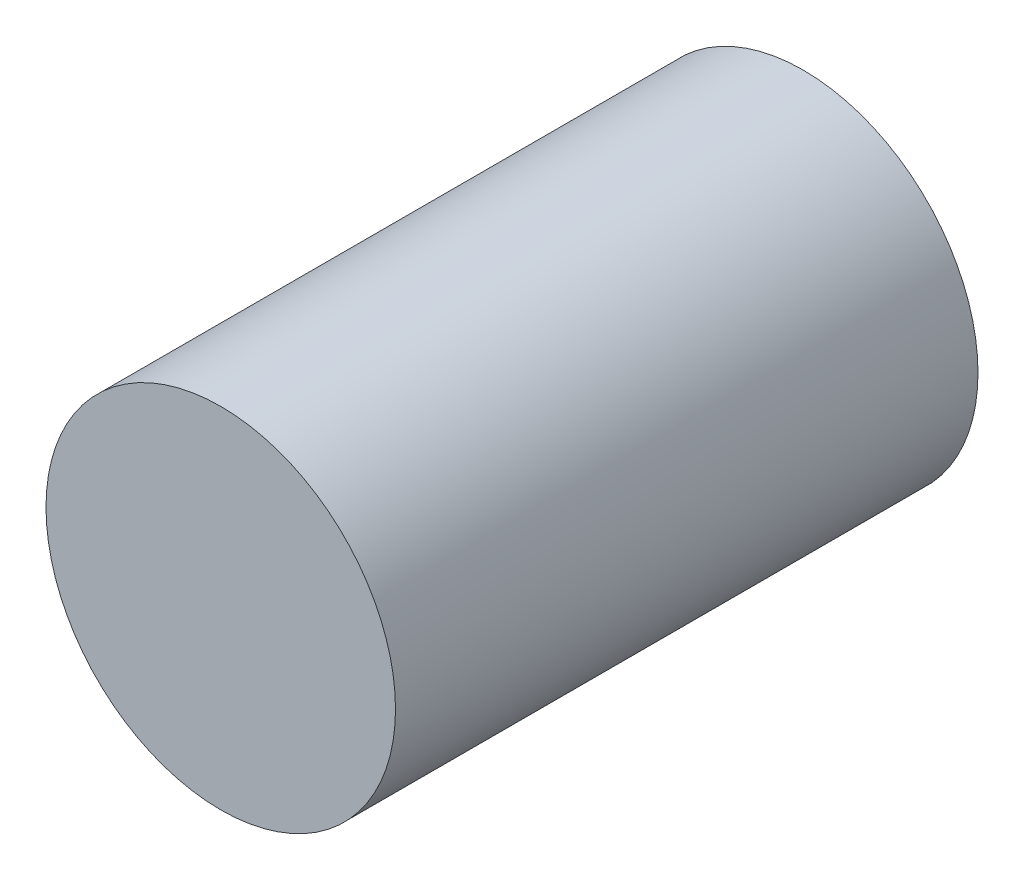
SolidWorks part; units mm, degrees
ref_plane "Front Plane" through (0, 0, 0) normal (1, 0, 0) x (0, 1, 0)
ref_plane "Top Plane" through (0, 0, 0) normal (0, 0, 1) x (0, 1, 0)
ref_plane "Right Plane" through (0, 0, 0) normal (0, 1, 0) x (-1, 0, 0)
sketch "Sketch1" plane through (0, 0, 0) normal (0, 0, 1) x (0, 1, 0)
  circle A0 centre (0, 0) radius 3
  dimension "D1" = 6
extrude "Boss-Extrude1" add sketch "Sketch1" along normal blind 10
